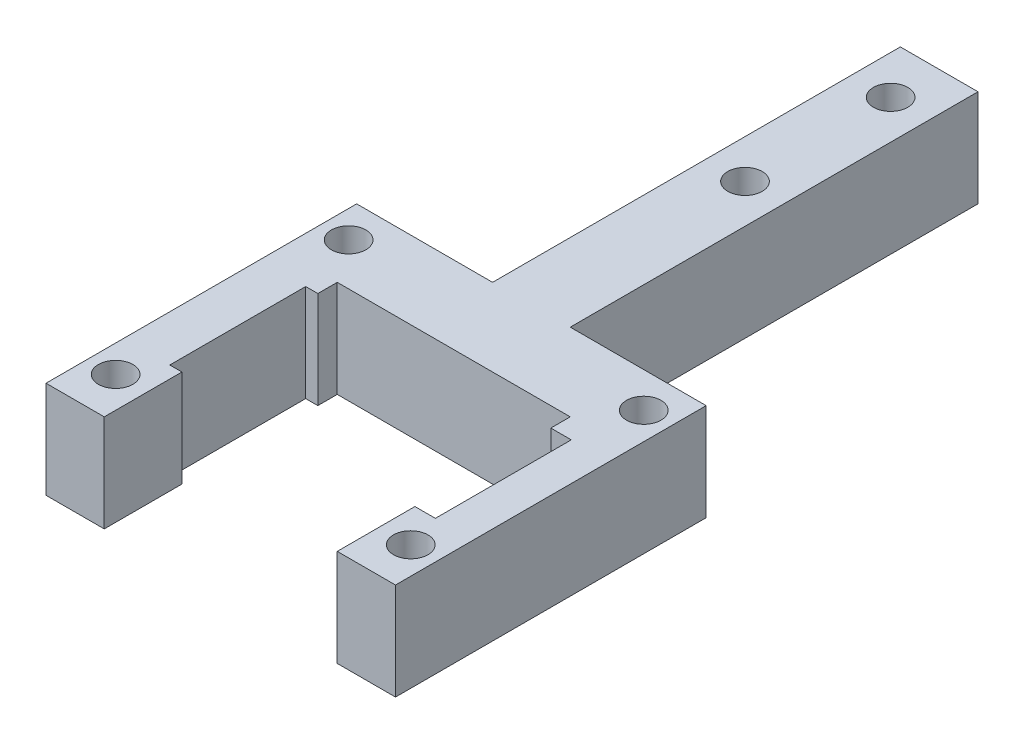
SolidWorks part; units mm, degrees
ref_plane "Front Plane" through (0, 0, 0) normal (0, 0, 1) x (1, 0, 0)
ref_plane "Top Plane" through (0, 0, 0) normal (0, 1, 0) x (1, 0, 0)
ref_plane "Right Plane" through (0, 0, 0) normal (1, 0, 0) x (0, 0, -1)
sketch "Sketch1" plane through (0, 0, 0) normal (0, 1, 0) x (1, 0, 0)
  line L0 (-4, 64.7737) -> (4, 64.7737)
  line L1 (4, 64.7737) -> (4, 22.7737)
  line L2 (4, 22.7737) -> (18, 22.7737)
  line L3 (18, 22.7737) -> (18, -9.2263)
  line L4 (18, -9.2263) -> (12, -9.2263)
  line L5 (12, -9.2263) -> (12, 14.7737)
  line L6 (12, 14.7737) -> (-12, 14.7737)
  line L7 (-12, 14.7737) -> (-12, -9.2263)
  line L8 (-12, -9.2263) -> (-18, -9.2263)
  line L9 (-18, -9.2263) -> (-18, 22.7737)
  line L10 (-18, 22.7737) -> (-4, 22.7737)
  line L11 (-4, 22.7737) -> (-4, 64.7737)
  line L12 (0, 72.4053) -> (0, -7.2263) construction
  line L13 (-4, 6.0721) -> (0, 6.0721) construction
  line L14 (0, 6.0721) -> (4, 6.0721) construction
  dimension "D1" = 8
  dimension "D2" = 6
  dimension "D3" = 8
  dimension "D4" = 42
  dimension "D5" = 32
  dimension "D6" = 36
extrude "Boss-Extrude1" add sketch "Sketch1" along normal blind 10
sketch "Sketch2" plane through (0, 10, 0) normal (0, 1, 0) x (1, 0, 0)
  line L0 (0, 64.7737) -> (0, 8.5432) construction
  line L1 (4, 64.7737) -> (-4, 64.7737) construction
  line L2 (18, 22.7737) -> (4, 22.7737) construction
  circle A0 centre (0, 44.7737) radius 1.775
  circle A1 centre (0, 59.7737) radius 1.775
  dimension "D3" = 3.55
  dimension "D1" = 22
  dimension "D2" = 15
extrude "Cut-Extrude1" cut sketch "Sketch2" against normal through all
sketch "Sketch3" plane through (0, 10, 0) normal (0, 1, 0) x (1, 0, 0)
  line L0 (-15.2, -4.8554) -> (-12, -4.8554) construction
  line L1 (-12, -9.2263) -> (-12, 14.7737) construction
  line L2 (12, -4.8554) -> (15.2, -4.8554) construction
  line L3 (12, 14.7737) -> (12, -9.2263) construction
  line L4 (-15.2, -4.8554) -> (-15.2, 19.1446) construction
  line L5 (15.2, -4.8554) -> (15.2, 19.1446) construction
  circle A0 centre (-15.2, -4.8554) radius 1.775
  circle A1 centre (15.2, -4.8554) radius 1.775
  circle A2 centre (-15.2, 19.1446) radius 1.775
  circle A3 centre (15.2, 19.1446) radius 1.775
  dimension "D1" = 3.55
  dimension "D2" = 30.4
  dimension "D3" = 24
extrude "Cut-Extrude2" cut sketch "Sketch3" against normal through all
sketch "Sketch4" plane through (0, 10, 0) normal (0, 1, 0) x (1, 0, 0)
  line L0 (-12, -9.2263) -> (-12, 14.7737) construction
  line L1 (-12, -1.2263) -> (-13.25, -1.2263)
  line L2 (-12, -1.2263) -> (-12, 12.7737)
  line L3 (-12, 12.7737) -> (-13.25, 12.7737)
  line L4 (-13.25, -1.2263) -> (-13.25, 12.7737)
  line L5 (12, 14.7737) -> (12, -9.2263) construction
  line L6 (12, -1.2263) -> (14.1063, -1.2263)
  line L7 (12, -1.2263) -> (12, 12.7737)
  line L8 (12, 12.7737) -> (14.1063, 12.7737)
  line L9 (14.1063, -1.2263) -> (14.1063, 12.7737)
  line L10 (-12, 14.7737) -> (12, 14.7737) construction
  dimension "D1" = 1.25
  dimension "D2" = 14
  dimension "D3" = 2
extrude "Cut-Extrude3" cut sketch "Sketch4" against normal through all
